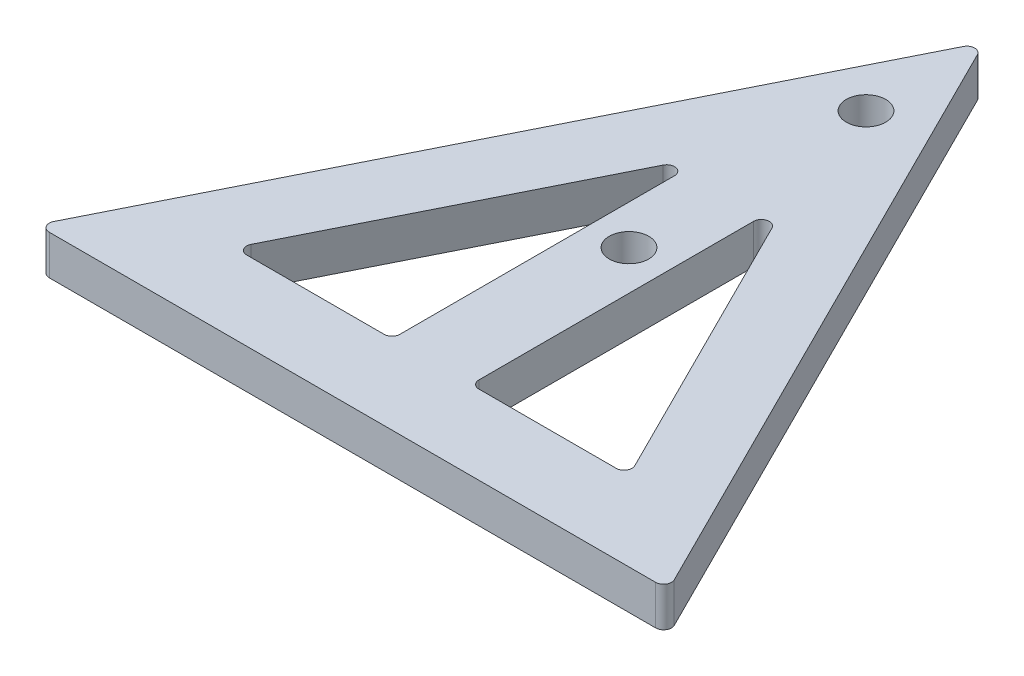
SolidWorks part; units mm, degrees
ref_plane "Front Plane" through (0, 0, 0) normal (0, 0, 1) x (1, 0, 0)
ref_plane "Top Plane" through (0, 0, 0) normal (0, 1, 0) x (1, 0, 0)
ref_plane "Right Plane" through (0, 0, 0) normal (1, 0, 0) x (0, 0, -1)
sketch "Sketch1" plane through (0, 0, 0) normal (0, 1, 0) x (1, 0, 0)
  line L0 (0, 0) -> (203.2, 0)
  line L1 (0, 0) -> (101.6, 203.198)
  line L2 (101.6, 203.198) -> (203.2, 0)
  dimension "D1" = 203.2
  dimension "D2" = 227.1827
extrude "Boss-Extrude1" add sketch "Sketch1" along normal blind 12.7
sketch "Sketch2" plane through (0, 0, 0) normal (0, 1, 0) x (1, 0, 0)
  line L1 (101.6, 203.198) -> (101.6, 0) construction
  line L2 (0, 0) -> (203.2, 0) construction
  line L3 (38.1, 25.4) -> (88.9, 25.4)
  line L4 (38.1, 25.4) -> (88.9, 127)
  line L6 (88.9, 25.4) -> (88.9, 127)
  line L7 (165.1, 25.4) -> (114.3, 25.4)
  line L8 (165.1, 25.4) -> (114.3, 127)
  line L9 (114.3, 25.4) -> (114.3, 127)
  circle A0 centre (101.6, 165.098) radius 6.35
  dimension "D5" = 12.7
  dimension "D6" = 38.1
  dimension "D1" = 25.4
  dimension "D2" = 50.8
  dimension "D3" = 101.6
  dimension "D4" = 12.7
extrude "Cut-Extrude5" cut sketch "Sketch2" along normal blind 12.7 contours L4 L6 L3 | L7 L9 L8 | A0
fillet "Fillet1" radius 2.54 3 edges at (0, 6.35, 0) (203.2, 6.35, 0) (101.6, 6.35, -203.198)
fillet "Fillet2" radius 2.54 6 edges at (165.1, 6.35, -25.4) (114.3, 6.35, -25.4) (114.3, 6.35, -127) (88.9, 6.35, -127) (88.9, 6.35, -25.4) (38.1, 6.35, -25.4)
sketch "Sketch3" plane through (0, 12.7, 0) normal (0, 1, 0) x (1, 0, 0)
  line L0 (4.1098, 0) -> (199.0902, 0) construction
  circle A0 centre (101.6, 88.9) radius 6.35
  dimension "D1" = 12.7
  dimension "D2" = 88.9
extrude "Cut-Extrude6" cut sketch "Sketch3" against normal blind 12.7
